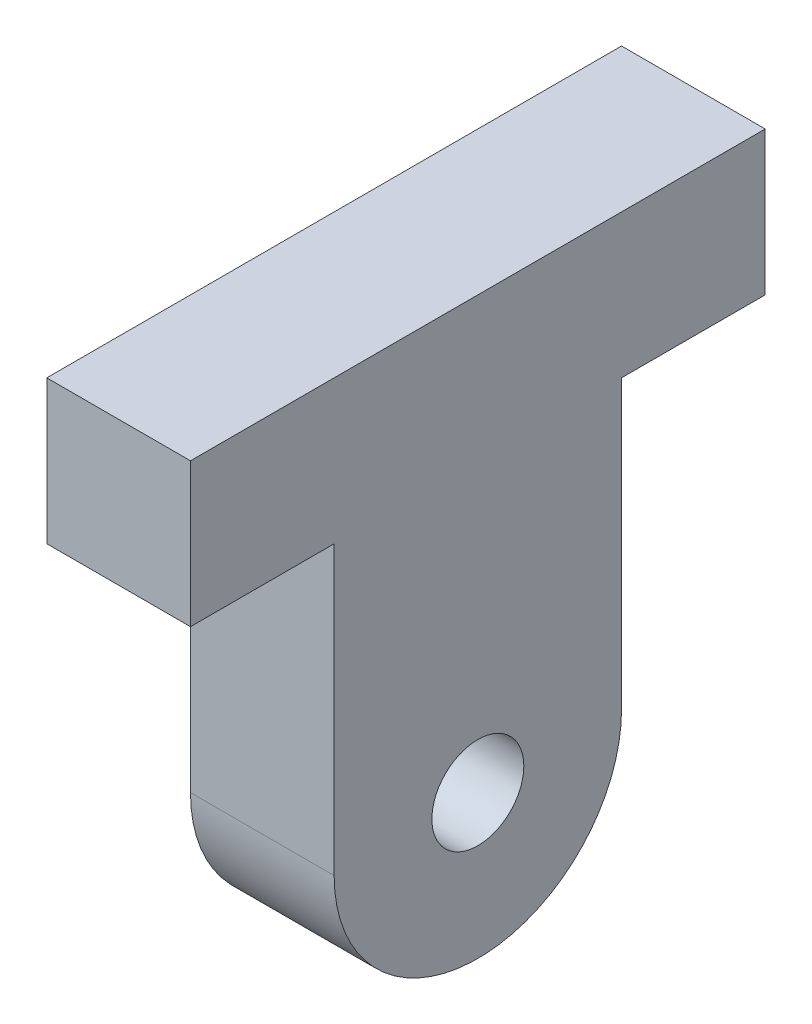
SolidWorks part; units mm, degrees
ref_plane "前视基准面" through (0, 0, 0) normal (0, 0, 1) x (1, 0, 0)
ref_plane "上视基准面" through (0, 0, 0) normal (0, 1, 0) x (1, 0, 0)
ref_plane "右视基准面" through (0, 0, 0) normal (1, 0, 0) x (0, 0, -1)
other "Configuration Table"
sketch "草图3" plane through (0, 0, 0) normal (1, 0, 0) x (0, 0, -1)
  line L0 (0, 0) -> (20, 0)
  line L1 (20, 0) -> (20, -5)
  line L2 (20, -5) -> (15, -5)
  line L3 (15, -5) -> (15, -15)
  line L4 (5, -15) -> (5, -5)
  line L5 (5, -5) -> (0, -5)
  line L6 (0, -5) -> (0, 0)
  arc A0 (15, -15) -> (5, -15) centre (10, -15) cw
  circle A1 centre (10, -15) radius 1.6
  dimension "D8" = 3.2
  dimension "D1" = 20
  dimension "D2" = 5
  dimension "D3" = 5
  dimension "D4" = 5
  dimension "D5" = 5
  dimension "D6" = 10
  dimension "D7" = 10
extrude "凸台-拉伸1" add sketch "草图3" along normal blind 5
